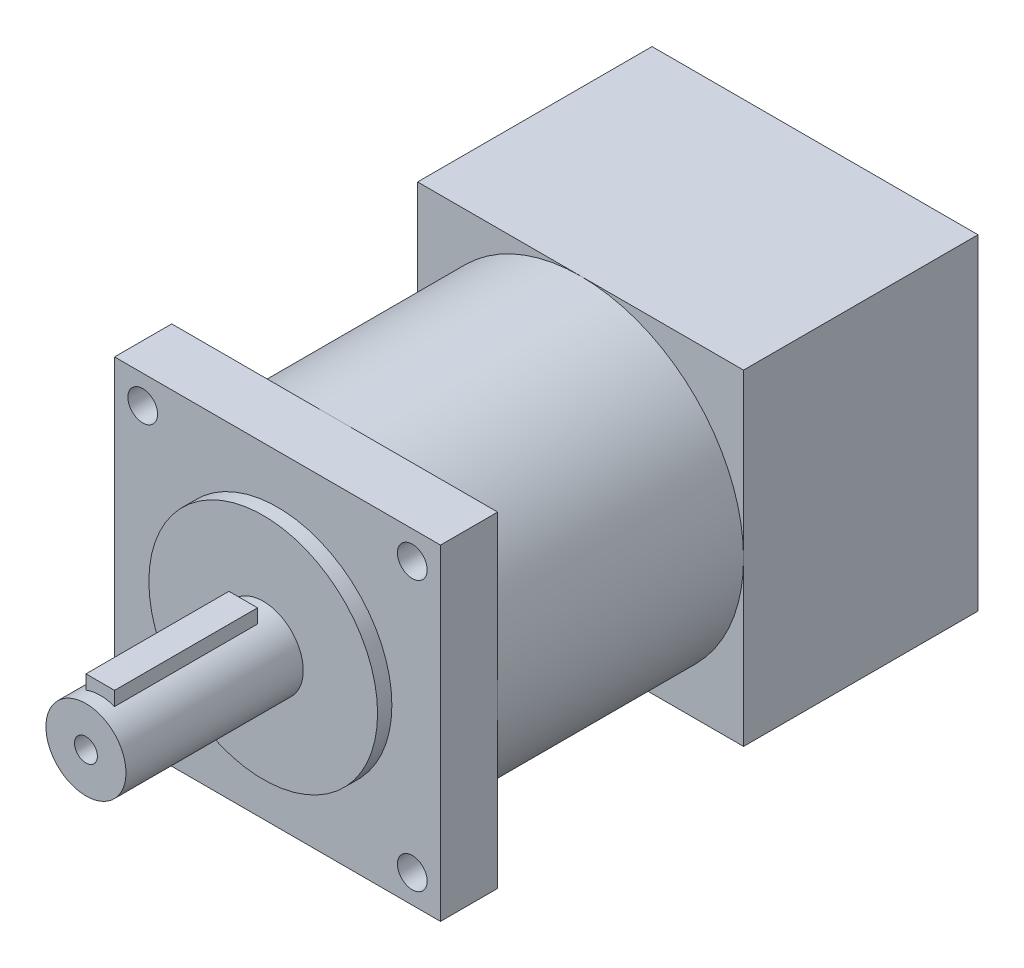
SolidWorks part; units mm, degrees
ref_plane "前视基准面" through (0, 0, 0) normal (0, 0, 1) x (1, 0, 0)
ref_plane "上视基准面" through (0, 0, 0) normal (0, 1, 0) x (1, 0, 0)
ref_plane "右视基准面" through (0, 0, 0) normal (1, 0, 0) x (0, 0, -1)
sketch "草图1" plane through (0, 0, 0) normal (0, 0, 1) x (1, 0, 0)
  line L1 (-28.5, 28.5) -> (28.5, 28.5)
  line L2 (-28.5, 28.5) -> (-28.5, -28.5)
  line L3 (-28.5, -28.5) -> (28.5, -28.5)
  line L4 (28.5, 28.5) -> (28.5, -28.5)
  line L5 (-28.5, 28.5) -> (28.5, -28.5) construction
  line L6 (-28.5, -28.5) -> (28.5, 28.5) construction
  point P0 (0, 0)
  dimension "D1" = 57
extrude "凸台-拉伸1" add sketch "草图1" along normal blind 41
sketch "草图2" plane through (0, 0, 41) normal (0, 0, 1) x (1, 0, 0)
  circle A0 centre (0, 0) radius 28.5
  dimension "D1" = 57
extrude "凸台-拉伸2" add sketch "草图2" along normal blind 53
sketch "草图3" plane through (0, 0, 94) normal (0, 0, 1) x (1, 0, 0)
  circle A0 centre (0, 0) radius 20
  dimension "D1" = 40
extrude "凸台-拉伸3" add sketch "草图3" along normal blind 2.5
sketch "草图4" plane through (0, 0, 96.5) normal (0, 0, 1) x (1, 0, 0)
  circle A0 centre (0, 0) radius 7
  dimension "D1" = 14
extrude "凸台-拉伸4" add sketch "草图4" along normal blind 31
sketch "草图7" plane through (0, 0, 94) normal (0, 0, 1) x (1, 0, 0)
  line L0 (-23.57, 23.57) -> (23.57, 23.57) construction
  line L1 (-28.5, -28.5) -> (28.5, -28.5)
  line L2 (-28.5, -28.5) -> (-28.5, 28.5)
  line L3 (-28.5, 28.5) -> (28.5, 28.5)
  line L4 (28.5, -28.5) -> (28.5, 28.5)
  line L5 (-28.5, -28.5) -> (28.5, 28.5) construction
  line L6 (-28.5, 28.5) -> (28.5, -28.5) construction
  circle A0 centre (-23.57, 23.57) radius 2.6
  circle A1 centre (23.57, 23.57) radius 2.6
  circle A2 centre (23.57, -23.57) radius 2.6
  circle A3 centre (-23.57, -23.57) radius 2.6
  point P0 (0, 0)
  dimension "D3" = 5.2
  dimension "D1" = 57
  dimension "D2" = 47.14
extrude "凸台-拉伸5" add sketch "草图7" against normal blind 10
ref_plane "基准面1" through (0, 0, 125) normal (0, 0, 1) x (1, 0, 0)
sketch "草图8" plane through (0, 0, 125) normal (0, 0, 1) x (1, 0, 0)
  line L1 (2.5, 5) -> (-2.5, 5)
  line L2 (2.5, 5) -> (2.5, 9)
  line L3 (2.5, 9) -> (-2.5, 9)
  line L4 (-2.5, 5) -> (-2.5, 9)
  line L5 (2.5, 5) -> (-2.5, 9) construction
  line L6 (2.5, 9) -> (-2.5, 5) construction
  circle A0 centre (0, 0) radius 7 construction
  circle A1 centre (0, 0) radius 7 construction
  point P0 (0, 7)
  dimension "D1" = 5
  dimension "D2" = 4
extrude "凸台-拉伸6" add sketch "草图8" against normal blind 25
sketch "草图9" plane through (0, 0, 127.5) normal (0, 0, 1) x (1, 0, 0)
  circle A0 centre (0, 0) radius 2
  dimension "D1" = 4
extrude "切除-拉伸1" cut sketch "草图9" against normal blind 6
